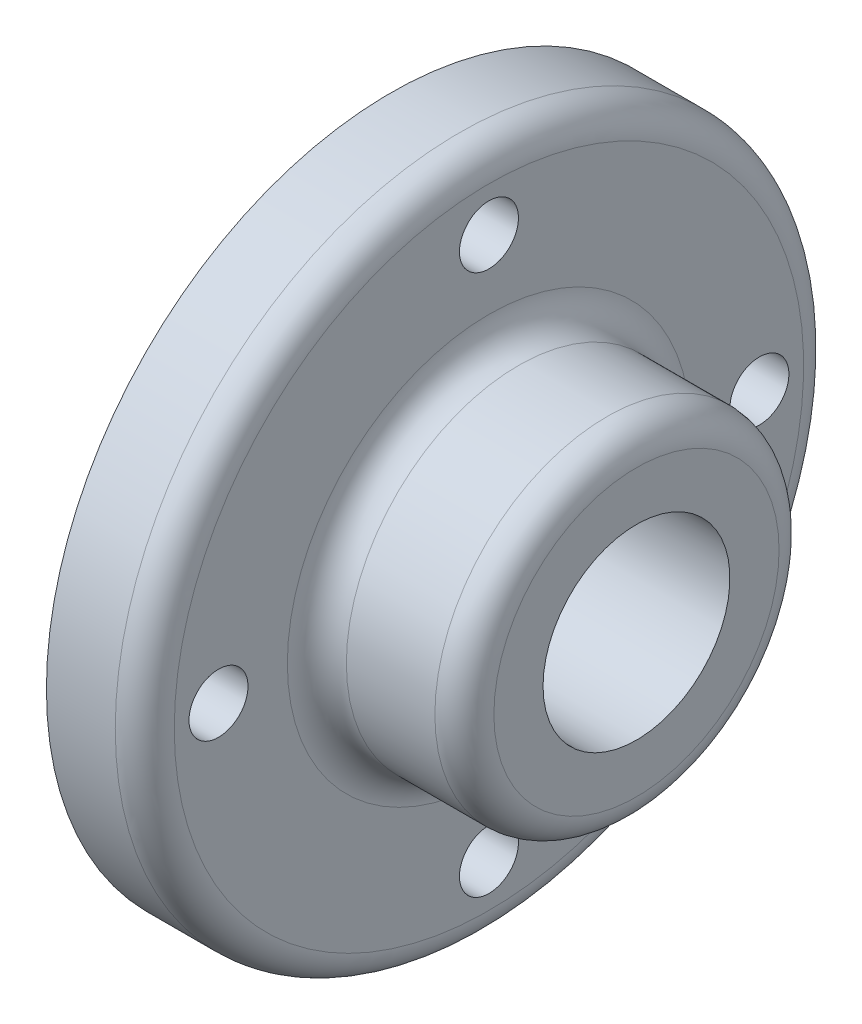
SolidWorks part; units mm, degrees
ref_plane "Front Plane" through (0, 0, 0) normal (0, 0, 1) x (1, 0, 0)
ref_plane "Top Plane" through (0, 0, 0) normal (0, 1, 0) x (1, 0, 0)
ref_plane "Right Plane" through (0, 0, 0) normal (1, 0, 0) x (0, 0, -1)
sketch "Sketch1" plane through (0, 0, 0) normal (0, 0, 1) x (1, 0, 0)
  line L0 (0, 0) -> (78.9501, 0) construction
  line L1 (0, 19) -> (0, 70)
  line L2 (20, 70) -> (20, 35)
  line L3 (20, 35) -> (50, 35)
  line L4 (50, 35) -> (50, 19)
  line L5 (50, 19) -> (0, 19)
  line L6 (0, 70) -> (20, 70)
  dimension "D1" = 20
  dimension "D2" = 50
  dimension "D3" = 38
  dimension "D4" = 140
  dimension "D5" = 70
revolve "Revolve1" add sketch "Sketch1" angle 360 about L0
fillet "Fillet1" radius 6 3 edges at (50, 0, 35) (20, 0, 35) (20, 0, 70)
hole_wizard "Ø12.0 (12) Diameter Hole1" positions "Sketch2" profile "Sketch3" hole size "Ø12.0" standard "DIN" end condition through all
sketch "Sketch2" plane through (0, 0, 0) normal (-1, 0, 0) x (0, 0, 1)
  point P0 (0, 55)
  dimension "D1" = 55
sketch "Sketch3" plane through (0, 55, 0) normal (0, 1, 0) x (0, 0, 1)
  line L0 (0, 0) -> (0, 50)
  line L1 (0, 50) -> (6, 50)
  line L2 (6, 50) -> (6, 0)
  line L5 (6, 0) -> (0, 0)
  line L11 (0, -6.35) -> (0, 107.95) construction
  dimension "Thru Hole Dia." = 12
  dimension "Thru Hole Depth" = 50
pattern_circular "CirPattern1" count 4 over 360 about axis through (0, 0, 0) along (1, 0, 0) of "Ø12.0 (12) Diameter Hole1"
